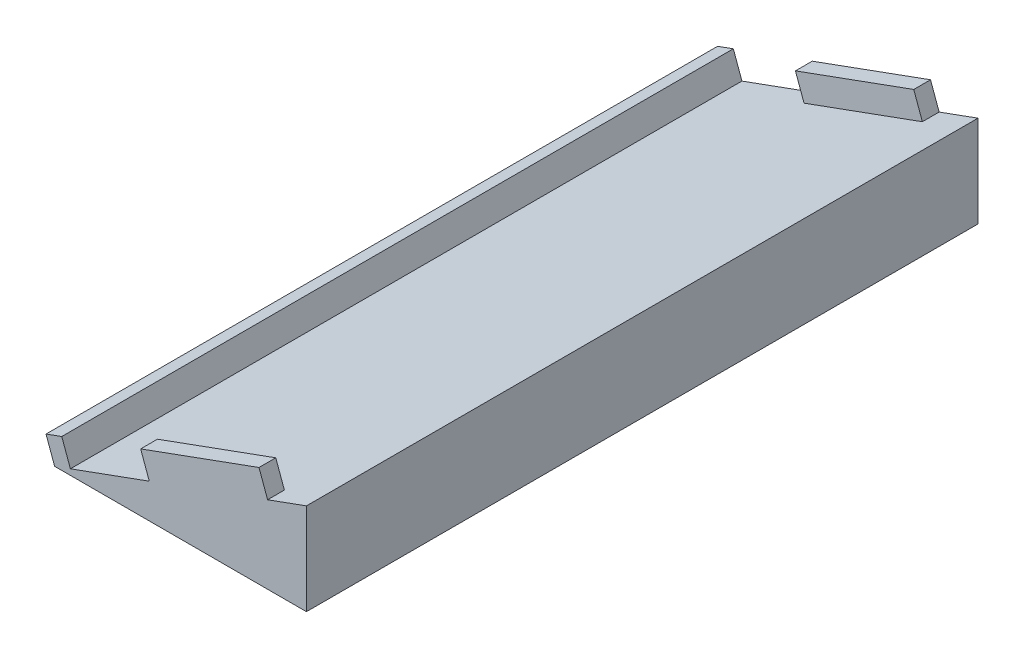
SolidWorks part; units mm, degrees
ref_plane "Front" through (0, 0, 0) normal (0, 0, 1) x (1, 0, 0)
ref_plane "Top" through (0, 0, 0) normal (0, 1, 0) x (1, 0, 0)
ref_plane "Right" through (0, 0, 0) normal (1, 0, 0) x (0, 0, -1)
sketch "Sketch1" plane through (0, 0, 0) normal (0, 0, 1) x (1, 0, 0)
  line L0 (0, 0) -> (30, 0)
  line L1 (0, 0) -> (30, 10.9191)
  line L2 (30, 10.9191) -> (30, 0)
  dimension "D1" = 30
  dimension "D2" = 20
extrude "Boss-Extrude1" add sketch "Sketch1" along normal blind 80
sketch "Sketch2" plane through (0, 0, 0) normal (-0.342, 0.9397, 0) x (0.9397, 0.342, 0)
  line L0 (31.9253, -80) -> (0, -80) construction
  line L1 (0, 0) -> (2, 0)
  line L2 (0, 0) -> (0, -80)
  line L3 (0, -80) -> (2, -80)
  line L4 (2, 0) -> (2, -80)
  line L5 (31.9253, 0) -> (0, 0) construction
  line L7 (12, 0) -> (27, 0)
  line L8 (12, 0) -> (12, -2)
  line L9 (12, -2) -> (27, -2)
  line L10 (27, 0) -> (27, -2)
  line L11 (12, -80) -> (27, -80)
  line L12 (12, -80) -> (12, -78)
  line L13 (12, -78) -> (27, -78)
  line L14 (27, -80) -> (27, -78)
  dimension "D1" = 2
  dimension "D2" = 2
  dimension "D3" = 15
  dimension "D4" = 10
  dimension "D5" = 2
  dimension "D6" = 15
extrude "Boss-Extrude2" add sketch "Sketch2" along normal blind 3
